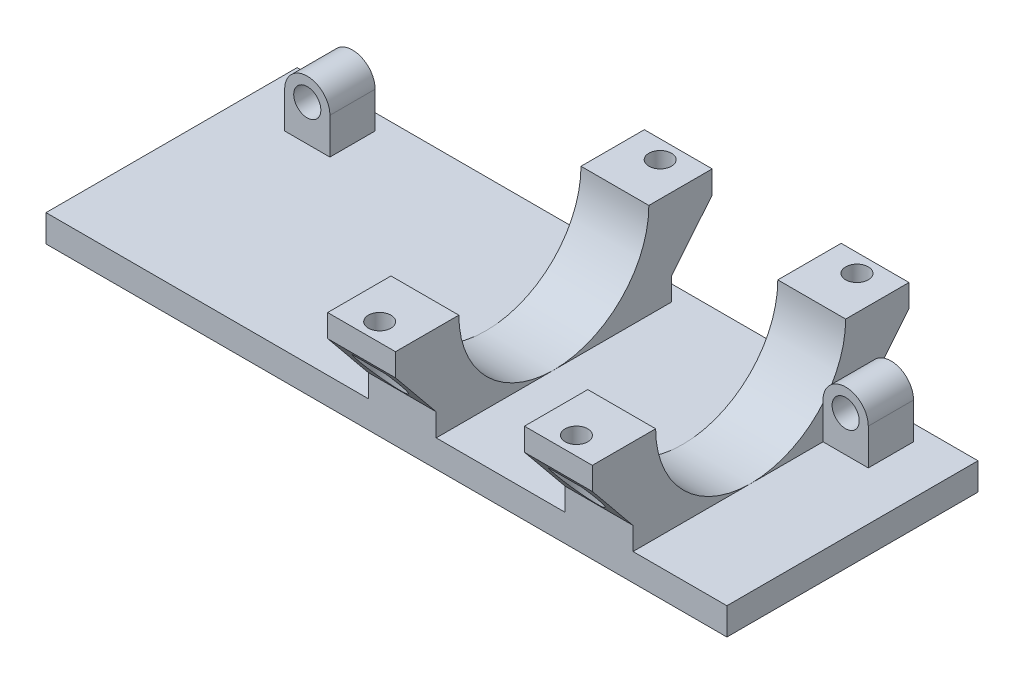
SolidWorks part; units mm, degrees
ref_plane "Alzado" through (0, 0, 0) normal (0, 0, 1) x (1, 0, 0)
ref_plane "Planta" through (0, 0, 0) normal (0, 1, 0) x (1, 0, 0)
ref_plane "Vista lateral" through (0, 0, 0) normal (1, 0, 0) x (0, 0, -1)
sketch "Croquis1" plane through (0, 0, 0) normal (0, 1, 0) x (1, 0, 0)
  line L1 (74.5, -26.5) -> (-74.5, -26.5)
  line L2 (74.5, -26.5) -> (74.5, 26.5)
  line L3 (74.5, 26.5) -> (-74.5, 26.5)
  line L4 (-74.5, -26.5) -> (-74.5, 26.5)
  line L5 (74.5, -26.5) -> (-74.5, 26.5) construction
  line L6 (74.5, 26.5) -> (-74.5, -26.5) construction
  point P0 (0, 0)
  dimension "D1" = 149
  dimension "D2" = 53
extrude "Saliente-Extruir1" add sketch "Croquis1" along normal blind 6
ref_plane "Plano1" through (51.5, 0, 0) normal (1, 0, 0) x (0, 0, -1)
sketch "Croquis2" plane through (51.5, 0, 0) normal (1, 0, 0) x (0, 0, -1)
  line L0 (-26.5, 6) -> (26.5, 6) construction
  line L1 (26, 6) -> (-26, 6)
  line L2 (26, 6) -> (26, 27)
  line L4 (-26, 6) -> (-26, 27)
  arc A0 (26, 27) -> (-26, 27) centre (0, 27) ccw
  point P6 (0, 6)
  dimension "D1" = 52
  dimension "D2" = 21
extrude "Saliente-Extruir2" add sketch "Croquis2" against normal blind 15 contours L2 A0 L4 L1
ref_plane "Plano4" through (8, 0, 0) normal (-1, 0, 0) x (0, 0, 1)
sketch "Croquis5" plane through (8, 0, 0) normal (-1, 0, 0) x (0, 0, 1)
  line L0 (-26, 6) -> (26, 6) construction
  line L1 (26, 6) -> (26, 27) construction
  line L2 (-26, 6) -> (-26, 27) construction
  line L3 (-26, 6) -> (26, 6)
  line L4 (26, 6) -> (26, 27)
  line L5 (-26, 6) -> (-26, 27)
  arc A0 (26, 27) -> (-26, 27) centre (0, 27) ccw construction
  arc A1 (26, 27) -> (-26, 27) centre (0, 27) ccw
extrude "Saliente-Extruir5" add sketch "Croquis5" along normal blind 15
sketch "Croquis3" plane through (51.5, 0, 0) normal (1, 0, 0) x (0, 0, -1)
  circle A0 centre (0, 27) radius 21
  dimension "D1" = 42
extrude "Cortar-Extruir2" cut sketch "Croquis3" against normal through all contours A0
ref_plane "Plano5" through (0, 0, 26) normal (0, 0, 1) x (1, 0, 0)
sketch "Croquis6" plane through (0, 0, -26) normal (0, 0, 1) x (1, 0, 0)
  line L0 (-74.5, 6) -> (74.5, 6) construction
  line L1 (61.5, 6) -> (51.5, 6)
  line L2 (61.5, 6) -> (61.5, 14)
  line L4 (51.5, 6) -> (51.5, 14)
  line L6 (51.5, 6) -> (51.5, 27) construction
  arc A0 (61.5, 14) -> (51.5, 14) centre (56.5, 14) ccw
  circle A1 centre (56.5, 14) radius 3
  dimension "D3" = 6
  dimension "D1" = 10
  dimension "D2" = 8
  dimension "D4" = 0
extrude "Saliente-Extruir11" add sketch "Croquis6" along normal blind 10 separate body
sketch "Croquis12" plane through (-74.5, 0, 0) normal (-1, 0, 0) x (0, 0, 1)
  line L4 (-26.5, 0) -> (26.5, 0)
  line L5 (26.5, 0) -> (26.5, 6)
  line L6 (26.5, 6) -> (-26.5, 6)
  line L7 (-26.5, 6) -> (-26.5, 0)
  line L8 (-26.5, 0) -> (26.5, 0)
  line L10 (26.5, 6) -> (-26.5, 6)
  line L11 (-26.5, 6) -> (-26.5, 0)
  line L14 (26.5, 0) -> (26.5, 6)
  dimension "D1" = 0
extrude "Saliente-Extruir24" add sketch "Croquis12" along normal blind 3.75
sketch "Croquis13" plane through (0, 0, -26.5) normal (0, 0, -1) x (-1, 0, 0)
  line L4 (-74.5, 0) -> (78.25, 0)
  line L5 (78.25, 0) -> (78.25, 6)
  line L6 (78.25, 6) -> (-74.5, 6)
  line L7 (-74.5, 6) -> (-74.5, 0)
  line L8 (-74.5, 0) -> (78.25, 0)
  line L9 (78.25, 0) -> (78.25, 6)
  line L10 (78.25, 6) -> (-74.5, 6)
  line L11 (-74.5, 6) -> (-74.5, 0)
  dimension "D1" = 0
extrude "Saliente-Extruir25" add sketch "Croquis13" along normal blind 3
sketch "Croquis14" plane through (0, 6, 0) normal (0, 1, 0) x (1, 0, 0)
  line L0 (-78.25, -26.5) -> (74.5, -26.5) construction
  line L1 (74.5, 29.5) -> (72.25, 29.5)
  line L2 (74.5, 29.5) -> (74.5, -26.5)
  line L3 (74.5, -26.5) -> (72.25, -26.5)
  line L4 (72.25, 29.5) -> (72.25, -26.5)
  dimension "D1" = 2.25
extrude "Cortar-Extruir3" cut sketch "Croquis14" against normal through all
ref_plane "Plano8" through (-3, 0, 0) normal (1, 0, 0) x (0, 0, -1)
mirror "Simetría2" about plane through (-3, 0, 0) normal (1, 0, 0) of bodies 108
sketch "Croquis17" plane through (0, 6, 0) normal (0, 1, 0) x (1, 0, 0)
  line L0 (72.25, 29.5) -> (72.25, -26.5) construction
  line L1 (-78.25, -26.5) -> (72.25, -26.5)
  line L2 (-78.25, -26.5) -> (-78.25, -26)
  line L3 (-78.25, -26) -> (72.25, -26)
  line L4 (72.25, -26.5) -> (72.25, -26)
  line L5 (-7, -26) -> (8, -26) construction
extrude "Cortar-Extruir4" cut sketch "Croquis17" against normal through all
ref_plane "Plano9" through (0, 27, 0) normal (0, 1, 0) x (1, 0, 0)
sketch "Croquis18" plane through (0, 27, 0) normal (0, 1, 0) x (1, 0, 0)
  line L0 (-78.25, -26) -> (-78.25, 29.5) construction
  line L1 (-27.75, 31.75) -> (72.25, 31.75)
  line L2 (-27.75, 31.75) -> (-27.75, -28.25)
  line L3 (-27.75, -28.25) -> (72.25, -28.25)
  line L4 (72.25, 31.75) -> (72.25, -28.25)
  point P7 (-78.25, 1.75)
  point P8 (-27.75, 1.75)
  dimension "D1" = 100
  dimension "D2" = 60
extrude "Cortar-Extruir5" cut sketch "Croquis18" along normal through all
sketch "Croquis19" plane through (51.5, 0, 0) normal (1, 0, 0) x (0, 0, -1)
  line L0 (-26, 27) -> (-35, 27)
  line L1 (3.85, 27) -> (-3.85, 27) construction
  line L2 (-26, 6) -> (-26, 27) construction
  line L4 (-26, 11) -> (-26, 27)
  line L5 (-35, 27) -> (-35, 22)
  line L7 (-35, 22) -> (-26, 11)
  dimension "D1" = 16
  dimension "D2" = 9
  dimension "D3" = 5
extrude "Saliente-Extruir27" add sketch "Croquis19" against normal blind 15
sketch "Croquis20" plane through (0, 27, 0) normal (0, 1, 0) x (1, 0, 0)
  line L0 (36.5, -35) -> (51.5, -35) construction
  line L1 (36.5, -21) -> (36.5, -35) construction
  circle A0 centre (44, -31) radius 2.5
  point P6 (0, 0)
  dimension "D1" = 5
  dimension "D2" = 4
  dimension "D3" = 7.5
extrude "Cortar-Extruir6" cut sketch "Croquis20" against normal blind 10
mirror "Simetría3" about plane through (0, 0, 0) normal (0, 0, 1) of "Cortar-Extruir6", "Saliente-Extruir27"
ref_plane "Plano10" through (22.25, 0, 0) normal (1, 0, 0) x (0, 0, -1)
mirror "Simetría6" about plane through (22.25, 0, 0) normal (1, 0, 0) of "Simetría3", "Cortar-Extruir6", "Saliente-Extruir27"
ref_plane "Plano11" through (0, 20.17, 0) normal (0, 1, 0) x (1, 0, 0)
sketch "Croquis21" plane through (0, 20.17, 0) normal (0, 1, 0) x (1, 0, 0)
  circle A0 centre (44, -31) radius 4.5
  dimension "D1" = 9
extrude "Cortar-Extruir7" cut sketch "Croquis21" against normal blind 10
mirror "Simetría7" about plane through (0, 0, 0) normal (0, 0, 1) of "Cortar-Extruir7" second plane through (22.25, 0, 0) second plane normal (1, 0, 0)
